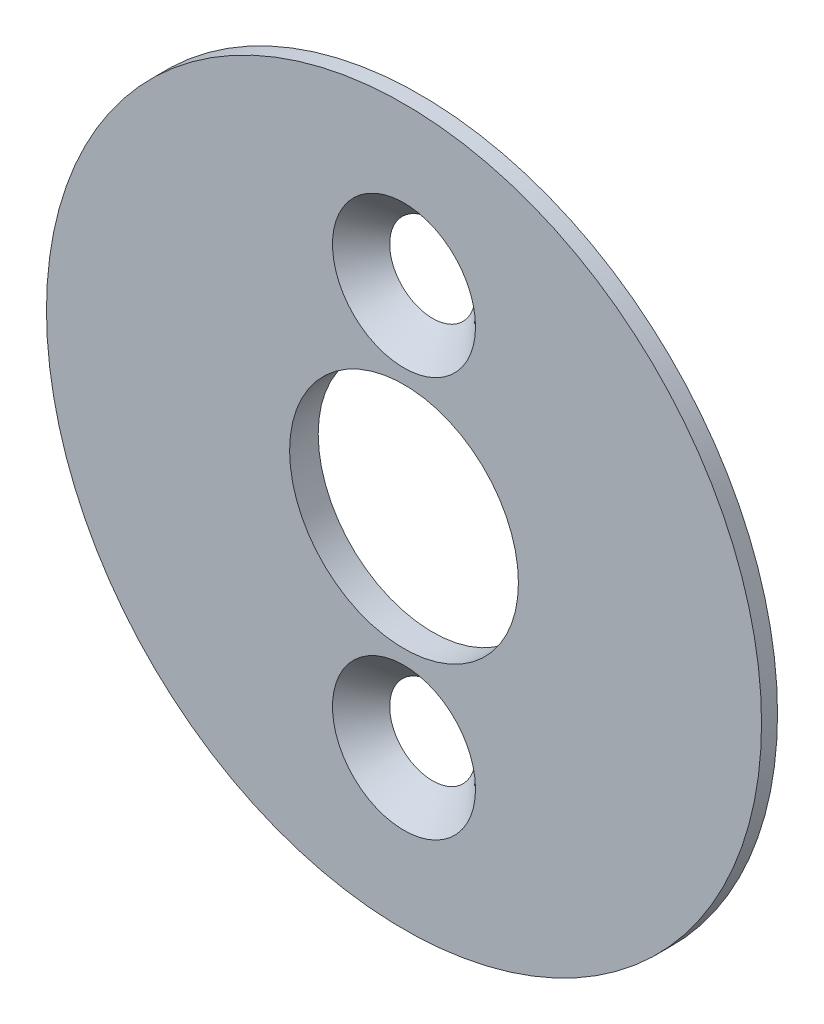
SolidWorks part; units mm, degrees
ref_plane "Front Plane" through (0, 0, 0) normal (0, 0, 1) x (1, 0, 0)
ref_plane "Top Plane" through (0, 0, 0) normal (0, 1, 0) x (1, 0, 0)
ref_plane "Right Plane" through (0, 0, 0) normal (1, 0, 0) x (0, 0, -1)
ref_axis "Axis1" through (0, 0, -0.1) along (0, 0, 1)
sketch "Sketch1" plane through (0, 0, 0) normal (0, 0, 1) x (1, 0, 0)
  circle A0 centre (0, 0) radius 12.5
extrude "Boss-Extrude1" add sketch "Sketch1" along normal blind 1
sketch "Sketch2" plane through (0, 0, 2) normal (-1, 0, 0) x (0, 0, 1)
  line L1 (-2, 10) -> (-1.5301, 12.665)
  line L2 (-2, 10) -> (-2, 12.665)
  line L3 (-2, 12.665) -> (-1.5301, 12.665)
  point P0 (0, 0)
revolve "Cut-Revolve1" cut sketch "Sketch2" angle 360 about axis through (0, 0, -0.1) along (0, 0, 1)
sketch "Sketch3" plane through (0, 0, 0) normal (0, 0, -1) x (-1, 0, 0)
  circle A0 centre (0, 0) radius 4
extrude "Cut-Extrude1" cut sketch "Sketch3" against normal up to next
sketch "Sketch4" plane through (0, 0, 1) normal (0, 0, 1) x (1, 0, 0)
  point P0 (0, 7)
  point P2 (0, -7)
  point P7 (0, 0)
hole_wizard "CSK for M3 Flat Countersunk Head Screw1" positions "Sketch4" profile "Sketch5" countersink size "M3" standard "JIS" end condition up to next
sketch "Sketch5" plane through (0, 7, 1) normal (1, 0, 0) x (0, -1, 0)
  line L0 (0, 0) -> (0, 1)
  line L1 (0, 1) -> (1.35, 1)
  line L2 (1.35, 1) -> (1.35, 1.15)
  line L3 (1.35, 1.15) -> (2.5, 0)
  line L5 (2.5, 0) -> (0, 0)
  line L6 (-1.35, 1.15) -> (-2.5, 0) construction
  line L11 (0, -6.35) -> (0, 107.95) construction
  dimension "Thru Hole Dia." = 2.7
  dimension "Thru Hole Depth" = 1
  dimension "Near C'Sink Dia." = 5
  dimension "Near C'Sink Angle" = 90
